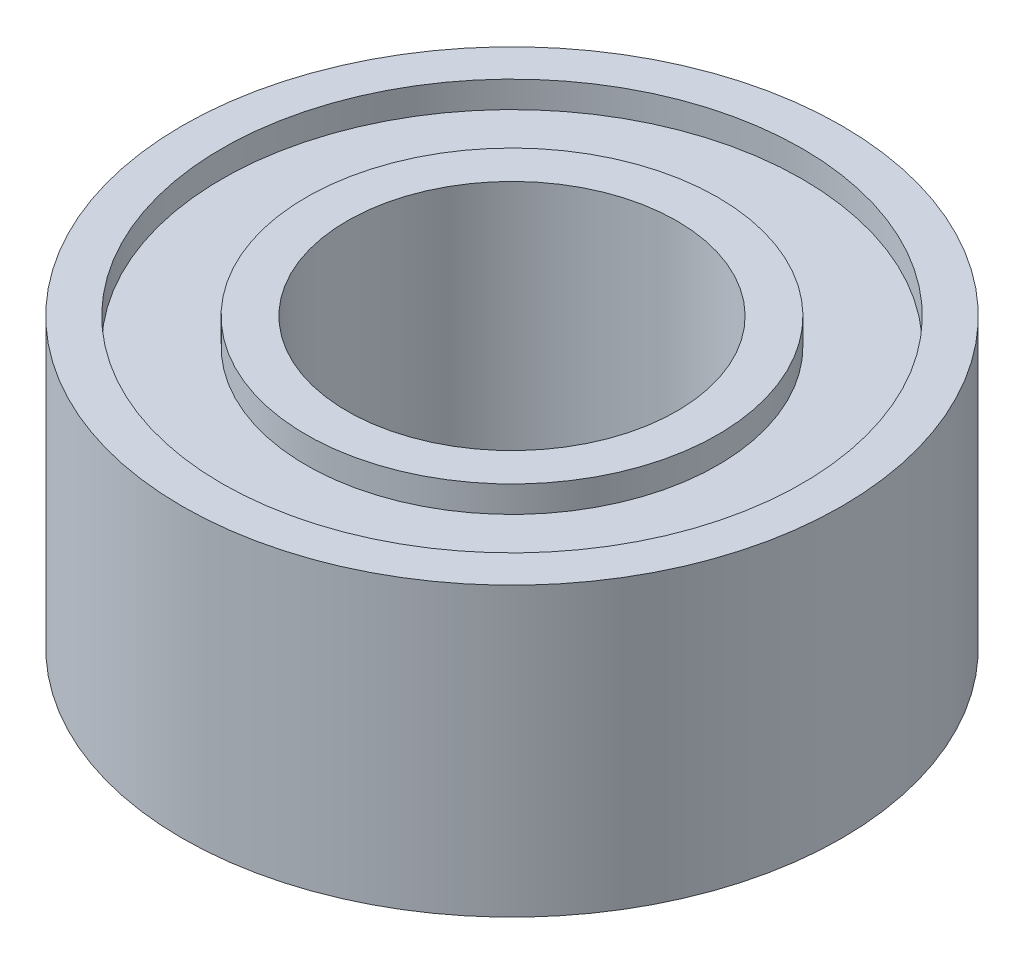
SolidWorks part; units mm, degrees
material "Chrome Stainless Steel"
ref_plane "Front Plane" through (0, 0, 0) normal (0, 0, 1) x (1, 0, 0)
ref_plane "Top Plane" through (0, 0, 0) normal (0, 1, 0) x (1, 0, 0)
ref_plane "Right Plane" through (0, 0, 0) normal (1, 0, 0) x (0, 0, -1)
sketch "Sketch1" plane through (0, 0, 0) normal (0, 0, 1) x (1, 0, 0)
  line L0 (1.9812, 1.3843) -> (1.5875, 1.3843)
  line L1 (1.5875, 1.3843) -> (1.5875, -1.3843)
  line L2 (1.5875, -1.3843) -> (1.9812, -1.3843)
  line L3 (1.9812, -1.3843) -> (1.9812, -1.1303)
  line L4 (1.9812, -1.1303) -> (2.794, -1.1303)
  line L5 (2.794, -1.1303) -> (2.794, -1.3843)
  line L6 (2.794, -1.3843) -> (3.175, -1.3843)
  line L7 (3.175, -1.3843) -> (3.175, 1.3843)
  line L8 (3.175, 1.3843) -> (2.794, 1.3843)
  line L9 (2.794, 1.3843) -> (2.794, 1.1303)
  line L10 (2.794, 1.1303) -> (1.9812, 1.1303)
  line L11 (1.9812, 1.1303) -> (1.9812, 1.3843)
  line L12 (0, 1.3843) -> (0, -1.3843) construction
revolve "Revolve1" add sketch "Sketch1" angle 360 about L12
